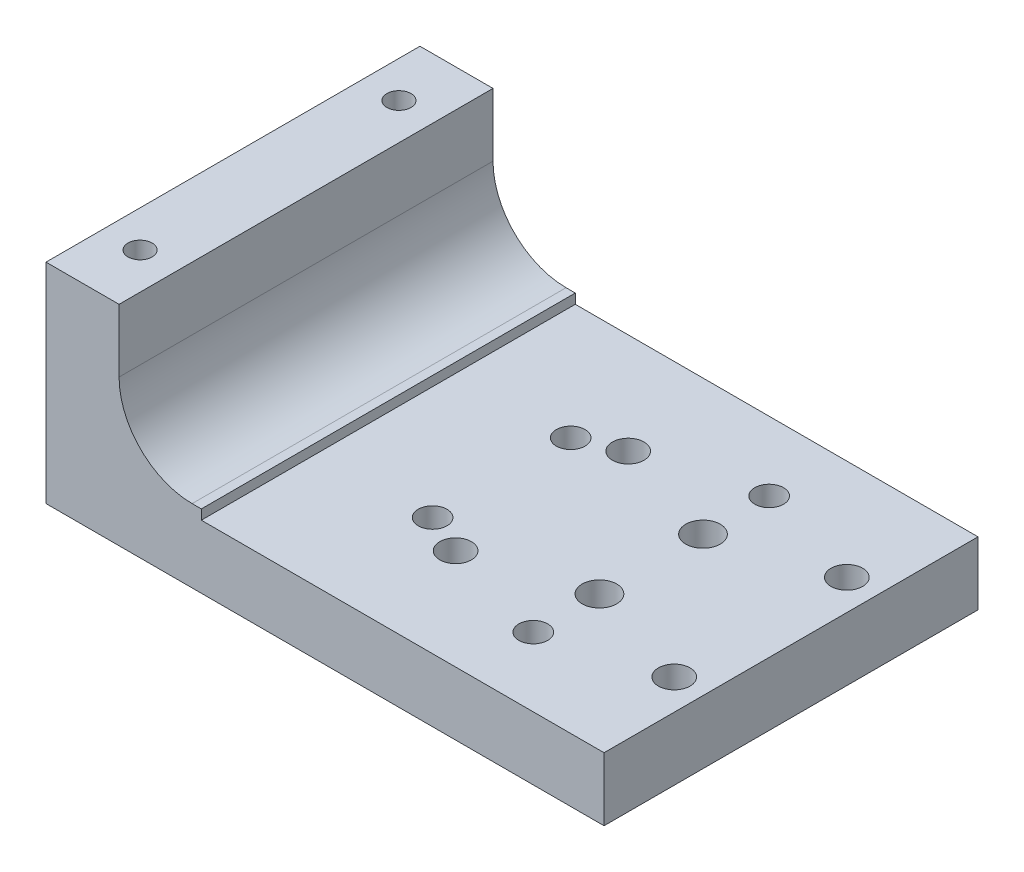
SolidWorks part; units mm, degrees
material "6061-T6 ALUMINUM"
ref_plane "Front/Back" through (0, 0, 0) normal (0, 0, 1) x (1, 0, 0)
ref_plane "Top/Bottom" through (0, 0, 0) normal (0, 1, 0) x (1, 0, 0)
ref_plane "Right/Left" through (0, 0, 0) normal (1, 0, 0) x (0, 0, -1)
sketch "Sketch1" plane through (0, 0, 0) normal (0, 0, 1) x (1, 0, 0)
  line L0 (0, 0) -> (97, 0)
  line L1 (0, 0) -> (0, 36.35)
  line L2 (0, 36.35) -> (12.7, 36.35)
  line L3 (12.7, 36.35) -> (12.7, 25.4)
  line L4 (25.4, 12.7) -> (97, 12.7)
  line L5 (97, 12.7) -> (97, 0)
  arc A0 (12.7, 25.4) -> (25.4, 12.7) centre (25.4, 25.4) ccw
  dimension "D1" = 12.7
  dimension "D2" = 12.7
  dimension "D3" = 36.35
  dimension "D4" = 97
extrude "Extrude1" add sketch "Sketch1" along normal mid plane 65
sketch "Sketch2" plane through (0, 0, -32.5) normal (0, 0, -1) x (-1, 0, 0)
  line L0 (0, 0) -> (-97, 0) construction
  line L1 (-97, 12.7) -> (-27, 12.7)
  line L2 (-97, 12.7) -> (-97, 11)
  line L3 (-97, 11) -> (-27, 11)
  line L4 (-27, 12.7) -> (-27, 11)
  dimension "D1" = 70
  dimension "D2" = 11
extrude "Cut-Extrude1" cut sketch "Sketch2" against normal through all
hole_wizard "M5 Clearance Hole1" positions "Sketch4" profile "Sketch3" hole size "M5" standard "_*ATS Preferred Ansi METRIC" end condition through all
sketch "Sketch4" plane through (0, 0, 0) normal (0, -1, 0) x (1, 0, 0)
  point P0 (53.7, 15)
  point P1 (91.7, 15)
  point P4 (91.7, -15)
  point P7 (53.7, -15)
sketch "Sketch3" plane through (53.7, 0, 15) normal (1, 0, 0) x (0, 0, -1)
  line L0 (0, 0) -> (0, 36.35)
  line L1 (0, 36.35) -> (2.75, 36.35)
  line L2 (2.75, 36.35) -> (2.75, 0)
  line L5 (2.75, 0) -> (0, 0)
  line L11 (0, -6.35) -> (0, 107.95) construction
  dimension "Thru Hole Dia." = 5.5
  dimension "Thru Hole Depth" = 36.35
hole_wizard "M5x0.8 Tapped Hole1" positions "Sketch6" profile "Sketch5" tap size "M5x0.8" standard "_*ATS Preferred Ansi METRIC"
sketch "Sketch6" plane through (0, 36.35, 0) normal (0, 1, 0) x (-1, 0, 0)
  line L0 (0, 0) -> (-12.7, 0) construction
  line L1 (-12.7, 32.5) -> (-12.7, -32.5) construction
  line L4 (-6.35, 0) -> (-6.35, 14.0998) construction
  point P0 (-6.35, 22.5)
  point P1 (-6.35, -22.5)
  dimension "D1" = 45
sketch "Sketch5" plane through (6.35, 36.35, 22.5) normal (1, 0, 0) x (0, 0, 1)
  line L0 (0, 0) -> (0, 20.3118)
  line L1 (0, 20.3118) -> (2.1, 19.05)
  line L2 (2.1, 19.05) -> (2.1, 0)
  line L5 (2.1, 0) -> (0, 0)
  line L10 (0, 20.3118) -> (-2.1, 19.05) construction
  line L11 (0, -6.35) -> (0, 107.95) construction
  dimension "Tap Drill Dia." = 4.2
  dimension "Tap Drill Depth" = 19.05
  dimension "Drill Angle" = 118
cosmetic thread "Hole Thread1"
cosmetic thread "Hole Thread2"
hole_wizard "Ø5.0 (5) Diameter Hole1" positions "Sketch8" profile "Sketch7" hole size "Ø5.0" standard "Ansi Metric" end condition up to next
sketch "Sketch8" plane through (0, 0, 0) normal (0, -1, 0) x (1, 0, 0)
  line L0 (49.2, -24) -> (49.2, 24) construction
  line L1 (50.2, 24) -> (59.2, 24) construction
  line L2 (50.2, -24) -> (59.2, -24) construction
  point P0 (46.7, 12)
  point P1 (46.7, -12)
  dimension "D1" = 2.5
  dimension "D2" = 12
  dimension "D3" = 12
sketch "Sketch7" plane through (46.7, 0, 12) normal (1, 0, 0) x (0, 0, -1)
  line L0 (0, 0) -> (0, 11)
  line L1 (0, 11) -> (2.5, 11)
  line L2 (2.5, 11) -> (2.5, 0)
  line L5 (2.5, 0) -> (0, 0)
  line L11 (0, -6.35) -> (0, 107.95) construction
  dimension "Thru Hole Dia." = 5
  dimension "Thru Hole Depth" = 11
hole_wizard "M6x1.0 Tapped Hole1" positions "Sketch10" profile "Sketch11" tap size "M6x1.0" standard "_*ATS Preferred Ansi METRIC" end condition through all
sketch "Sketch10" plane through (0, 0, 0) normal (0, -1, 0) x (1, 0, 0)
  line L0 (91.7, 15) -> (53.7, 15) construction
  line L2 (72.7, 15) -> (72.7, 27.5915) construction
  line L5 (0, 32.5) -> (97, 32.5) construction
  line L6 (0, -32.5) -> (97, -32.5) construction
  point P0 (72.7, 20.5)
  point P1 (72.7, -20.5)
  dimension "D1" = 12
  dimension "D2" = 12
sketch "Sketch11" plane through (72.7, 0, 20.5) normal (1, 0, 0) x (0, 0, -1)
  line L0 (0, 0) -> (0, 36.35)
  line L1 (0, 36.35) -> (2.5, 36.35)
  line L2 (2.5, 36.35) -> (2.5, 0)
  line L5 (2.5, 0) -> (0, 0)
  line L11 (0, -6.35) -> (0, 107.95) construction
  dimension "Thru Tap Drill Dia." = 5
  dimension "Thru Tap Drill Depth" = 36.35
cosmetic thread "Hole Thread3"
cosmetic thread "Hole Thread4"
hole_wizard "Ø6.0 (6) Diameter Hole1" positions "Sketch13" profile "Sketch12" hole size "Ø6.0" standard "Ansi Metric" end condition through all
sketch "Sketch13" plane through (0, 0, 0) normal (0, -1, 0) x (1, 0, 0)
  line L0 (72.7, 20.5) -> (72.7, -20.5) construction
  line L3 (72.7, 0) -> (82.611, 0) construction
  point P0 (72.7, -9)
  point P1 (72.7, 9)
  dimension "D1" = 18
sketch "Sketch12" plane through (72.7, 0, -9) normal (1, 0, 0) x (0, 0, -1)
  line L0 (0, 0) -> (0, 36.35)
  line L1 (0, 36.35) -> (3, 36.35)
  line L2 (3, 36.35) -> (3, 0)
  line L5 (3, 0) -> (0, 0)
  line L11 (0, -6.35) -> (0, 107.95) construction
  dimension "Thru Hole Dia." = 6
  dimension "Thru Hole Depth" = 36.35
